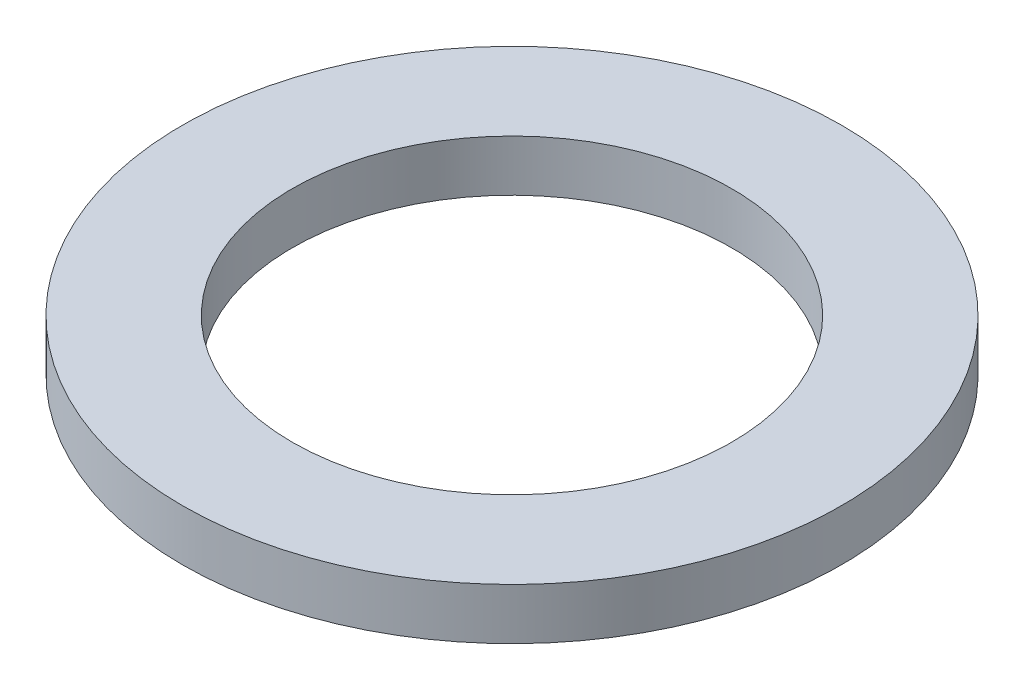
SolidWorks part; units mm, degrees
material "6061 Alloy"
ref_plane "Front Plane" through (0, 0, 0) normal (0, 0, 1) x (1, 0, 0)
ref_plane "Top Plane" through (0, 0, 0) normal (0, 1, 0) x (1, 0, 0)
ref_plane "Right Plane" through (0, 0, 0) normal (1, 0, 0) x (0, 0, -1)
sketch "Sketch1" plane through (0, 0, 0) normal (0, 1, 0) x (1, 0, 0)
  circle A0 centre (0, 0) radius 7.62
  circle A1 centre (0, 0) radius 11.43
  dimension "D1" = 15.24
  dimension "D2" = 3.81
extrude "Boss-Extrude1" add sketch "Sketch1" along normal blind 1.778
